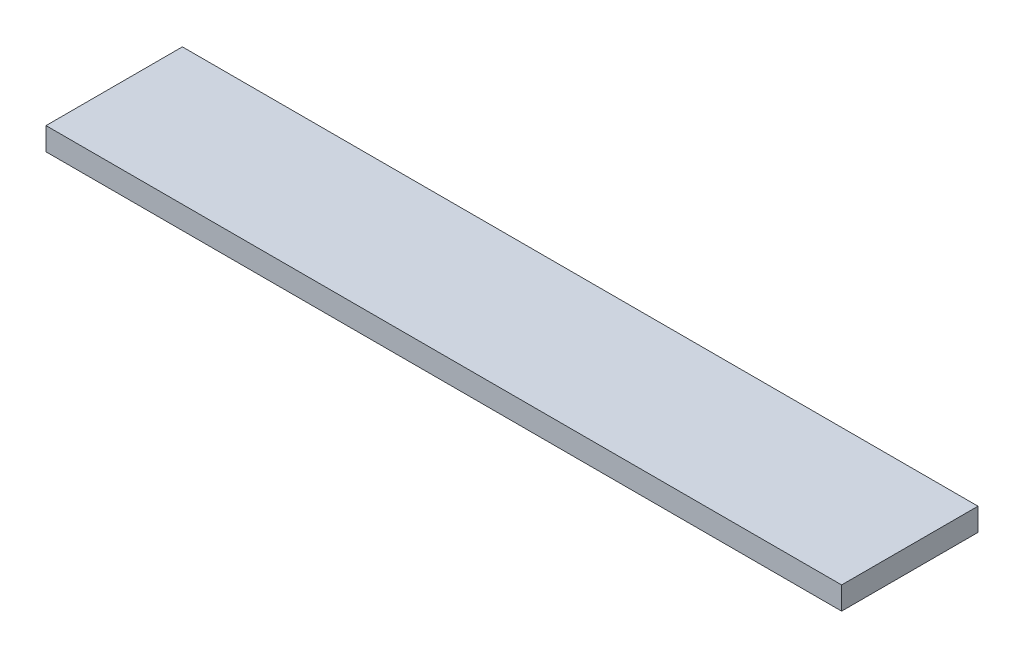
SolidWorks part; units mm, degrees
ref_plane "Front Plane" through (0, 0, 0) normal (0, 0, 1) x (1, 0, 0)
ref_plane "Top Plane" through (0, 0, 0) normal (0, 1, 0) x (1, 0, 0)
ref_plane "Right Plane" through (0, 0, 0) normal (1, 0, 0) x (0, 0, -1)
sketch "Sketch1" plane through (0, 0, 0) normal (0, 0, 1) x (1, 0, 0)
  line L1 (-22.3111, 16.1056) -> (12.6889, 16.1056)
  line L2 (-22.3111, 16.1056) -> (-22.3111, 10.1056)
  line L3 (-22.3111, 10.1056) -> (12.6889, 10.1056)
  line L4 (12.6889, 16.1056) -> (12.6889, 10.1056)
  line L5 (-4.8111, 10.1056) -> (-4.8111, 16.1056) construction
  line L6 (-22.3111, 13.1056) -> (12.6889, 13.1056) construction
  point P104 (-4.8111, 13.1056)
  dimension "D1" = 6
  dimension "D2" = 35
extrude "Boss-Extrude1" add sketch "Sketch1" along normal blind 1
move or copy body "Body-Move/Copy1" bodies to move or copy 102 copy no rotation origin (0, 13.1056, 0.25) rotation axis (1, 0, 0) rotation angle 90
